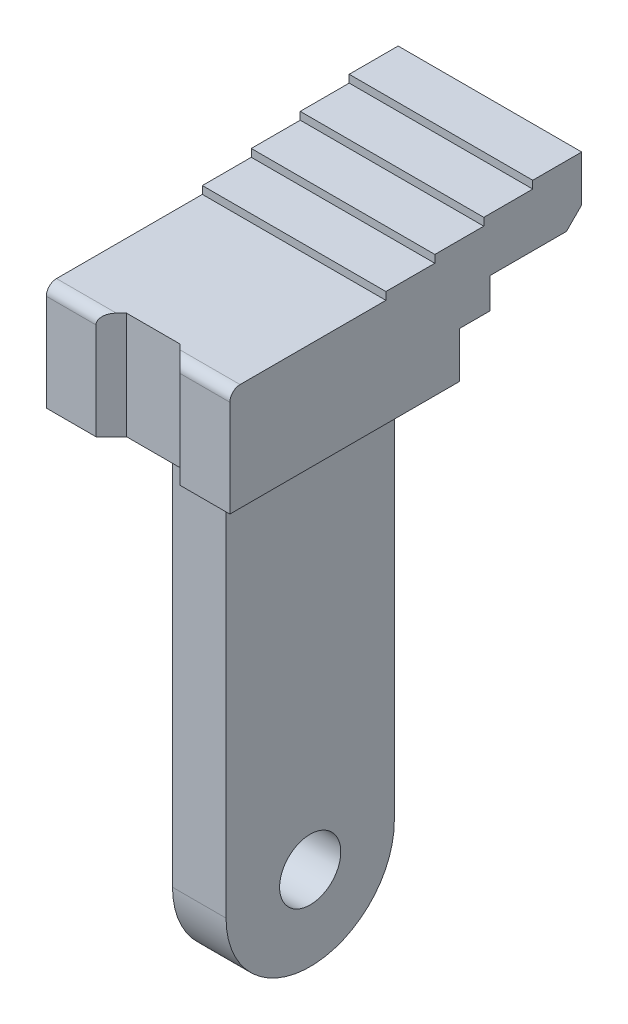
SolidWorks part; units mm, degrees
ref_plane "Front Plane" through (0, 0, 0) normal (0, 0, 1) x (1, 0, 0)
ref_plane "Top Plane" through (0, 0, 0) normal (0, 1, 0) x (1, 0, 0)
ref_plane "Right Plane" through (0, 0, 0) normal (1, 0, 0) x (0, 0, -1)
sketch "Sketch1" plane through (0, 0, 0) normal (1, 0, 0) x (0, 0, -1)
  line L0 (-3.75, -3) -> (3.75, -3) construction
  line L1 (-3.75, -3) -> (-3.75, 13) construction
  line L2 (3.75, -3) -> (3.75, 7) construction
  line L3 (-3.75, 13) -> (2.75, 13) construction
  line L4 (2.75, 13) -> (2.75, 7) construction
  line L5 (3.75, 7) -> (2.75, 7) construction
  line L6 (2.75, 0) -> (2.75, 15)
  line L7 (-2.75, 0) -> (-2.75, 13.5)
  line L8 (2.75, 15) -> (3.75, 15)
  line L9 (3.75, 15) -> (3.75, 16)
  line L16 (2.625, 18) -> (2.625, 21.9136) construction
  line L17 (1.495, 18) -> (1.495, 21.0229) construction
  line L18 (0.365, 18) -> (0.365, 20.8505) construction
  line L19 (-0.765, 18) -> (-0.765, 20.2758) construction
  line L20 (-4.75, 18) -> (3.75, 18) construction
  line L22 (6.75, 16.5) -> (6.75, 18)
  line L24 (3.75, 16) -> (6.25, 16)
  line L25 (-2.75, 13.5) -> (-4.75, 13.5)
  line L26 (-4.75, 13.5) -> (-4.75, 17)
  line L27 (-4.75, 17) -> (0.35, 17)
  line L28 (4.75, 17) -> (2.75, 17) construction
  line L29 (4.75, 17) -> (6.75, 17) construction
  line L37 (6.75, 18) -> (5.15, 18)
  line L38 (5.15, 17.75) -> (3.55, 17.75)
  line L39 (0.35, 17.25) -> (1.95, 17.25)
  line L40 (1.95, 17.5) -> (3.55, 17.5)
  line L41 (5.15, 18) -> (5.15, 17.75)
  line L42 (3.55, 17.75) -> (3.55, 17.5)
  line L43 (1.95, 17.5) -> (1.95, 17.25)
  line L44 (0.35, 17.25) -> (0.35, 17)
  line L45 (6.75, 16.5) -> (6.25, 16)
  circle A0 centre (0, 0) radius 1
  arc A1 (-2.75, 0) -> (2.75, 0) centre (0, 0) ccw
  point P5 (0, -3)
  point P49 (2.75, 17.5)
  dimension "D1" = 2
  dimension "D7" = 5.5
  dimension "D2" = 7.5
  dimension "D3" = 3
  dimension "D4" = 16
  dimension "D5" = 10
  dimension "D6" = 6.5
  dimension "D8" = 0.5
  dimension "D9" = 2
  dimension "D10" = 5
  dimension "D11" = 4
  dimension "D12" = 1
  dimension "D13" = 0.5
  dimension "D14" = 1
  dimension "D15" = 0.5
  dimension "D16" = 2
extrude "Boss-Extrude1" add sketch "Sketch1" along normal mid plane 6
sketch "Sketch2" plane through (0, 0, 4.75) normal (0, 0, 1) x (1, 0, 0)
  line L0 (0.875, -2.75) -> (0.875, 13.5)
  line L1 (-3, -2.75) -> (3, -2.75) construction
  line L2 (-0.875, -2.75) -> (-0.875, 13.5)
  line L3 (-0.875, -2.75) -> (-3, -2.75)
  line L4 (0.875, -2.75) -> (3, -2.75)
  line L5 (-0.875, -2.75) -> (0.875, -2.75) construction
  line L6 (3, 13.5) -> (-3, 13.5) construction
  line L7 (3, 13.5) -> (-3, 13.5) construction
  line L8 (0.875, 13.5) -> (3, 13.5)
  line L9 (3, 13.5) -> (3, -2.75)
  line L10 (-0.875, 13.5) -> (-3, 13.5)
  line L11 (-3, 13.5) -> (-3, -2.75)
  dimension "D1" = 1.75
extrude "Cut-Extrude1" cut sketch "Sketch2" against normal through all
sketch "Sketch3" plane through (0, 17, 0) normal (0, 1, 0) x (1, 0, 0)
  line L0 (-0.875, -4.25) -> (0.875, -4.25)
  line L1 (-0.875, -4.25) -> (-1.375, -4.75)
  line L2 (3, -4.75) -> (-3, -4.75) construction
  line L3 (0.875, -4.25) -> (1.375, -4.75)
  line L4 (-1.375, -4.75) -> (1.375, -4.75)
  point P2 (0, -4.25)
  dimension "D1" = 1.75
  dimension "D2" = 0.5
extrude "Cut-Extrude2" cut sketch "Sketch3" against normal up to surface (3.5 mm away) up to face at (0, 13.5, 0.5)
fillet "Fillet1" radius 0.3333 2 edges at (-2.1875, 17, 4.75) (2.1875, 17, 4.75)
